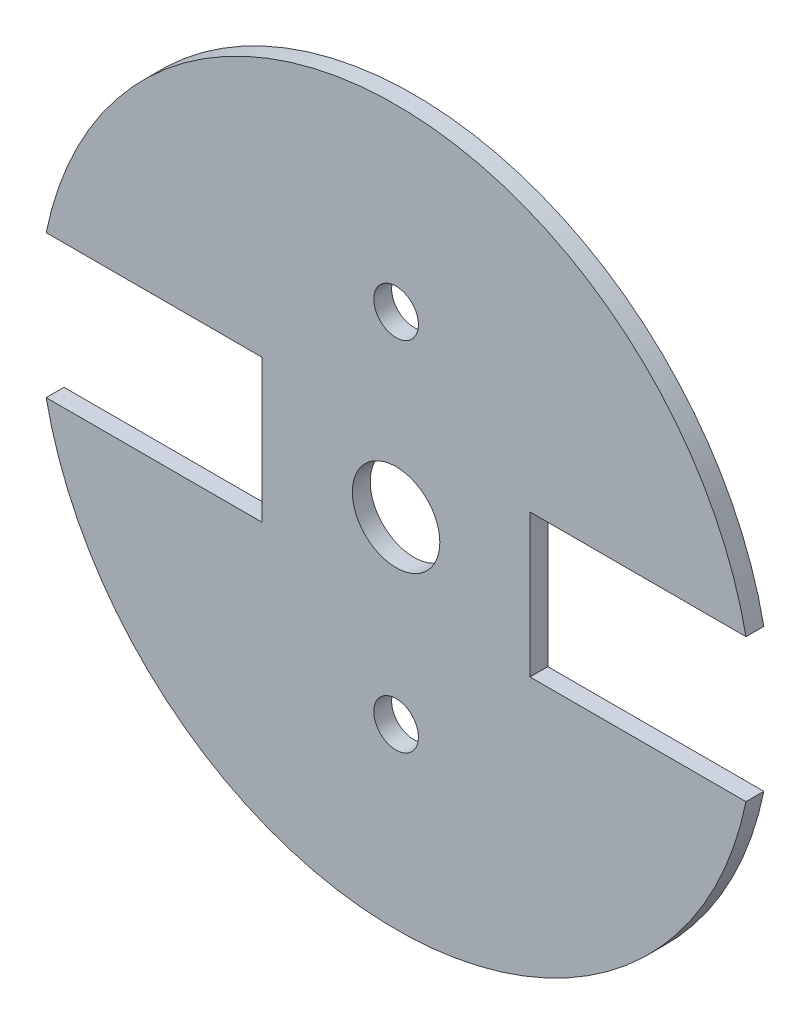
SolidWorks part; units mm, degrees
ref_plane "Front Plane" through (0, 0, 0) normal (0, 0, 1) x (1, 0, 0)
ref_plane "Top Plane" through (0, 0, 0) normal (0, 1, 0) x (1, 0, 0)
ref_plane "Right Plane" through (0, 0, 0) normal (1, 0, 0) x (0, 0, -1)
sketch "Sketch1" plane through (0, 0, 0) normal (0, 0, 1) x (1, 0, 0)
  line L0 (-15, 8) -> (-39.1918, 8)
  line L5 (-15, -8) -> (-39.1918, -8)
  line L8 (15, 8) -> (39.1918, 8)
  line L9 (15, -8) -> (39.1918, -8)
  line L10 (15, 8) -> (15, -8)
  line L11 (-15, 8) -> (-15, -8)
  arc A0 (-39.1918, -8) -> (39.1918, -8) centre (0, 0) ccw
  circle A1 centre (0, 19.9087) radius 2.5
  circle A2 centre (0, -20.0913) radius 2.5
  circle A3 centre (0, 0) radius 4.9
  arc A4 (39.1918, 8) -> (-39.1918, 8) centre (0, 0) ccw
extrude "Boss-Extrude1" add sketch "Sketch1" along normal blind 2
